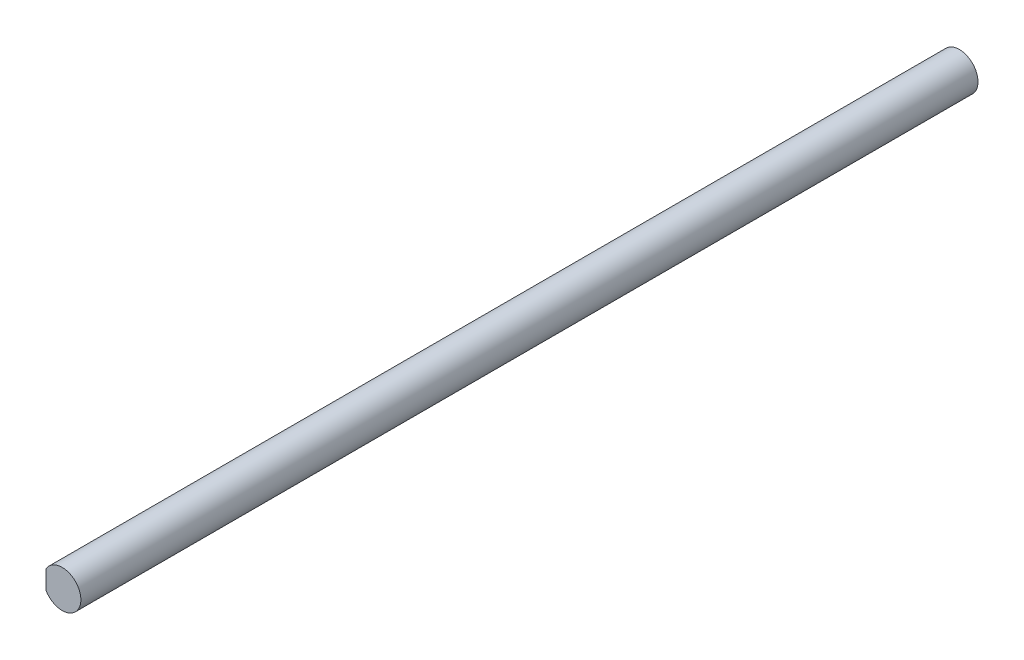
SolidWorks part; units mm, degrees
ref_plane "Front Plane" through (0, 0, 0) normal (0, 0, 1) x (1, 0, 0)
ref_plane "Top Plane" through (0, 0, 0) normal (0, 1, 0) x (1, 0, 0)
ref_plane "Right Plane" through (0, 0, 0) normal (1, 0, 0) x (0, 0, -1)
sketch "Sketch2" plane through (0, 0, 0) normal (0, 0, 1) x (1, 0, 0)
  line L0 (-2.7496, 1.5875) -> (-2.7496, -1.5875)
  arc A0 (-2.7496, -1.5875) -> (-2.7496, 1.5875) centre (0, 0) ccw
  dimension "D1" = 6.35
  dimension "D2" = 3.175
extrude "Boss-Extrude1" add sketch "Sketch2" along normal blind 152.4
